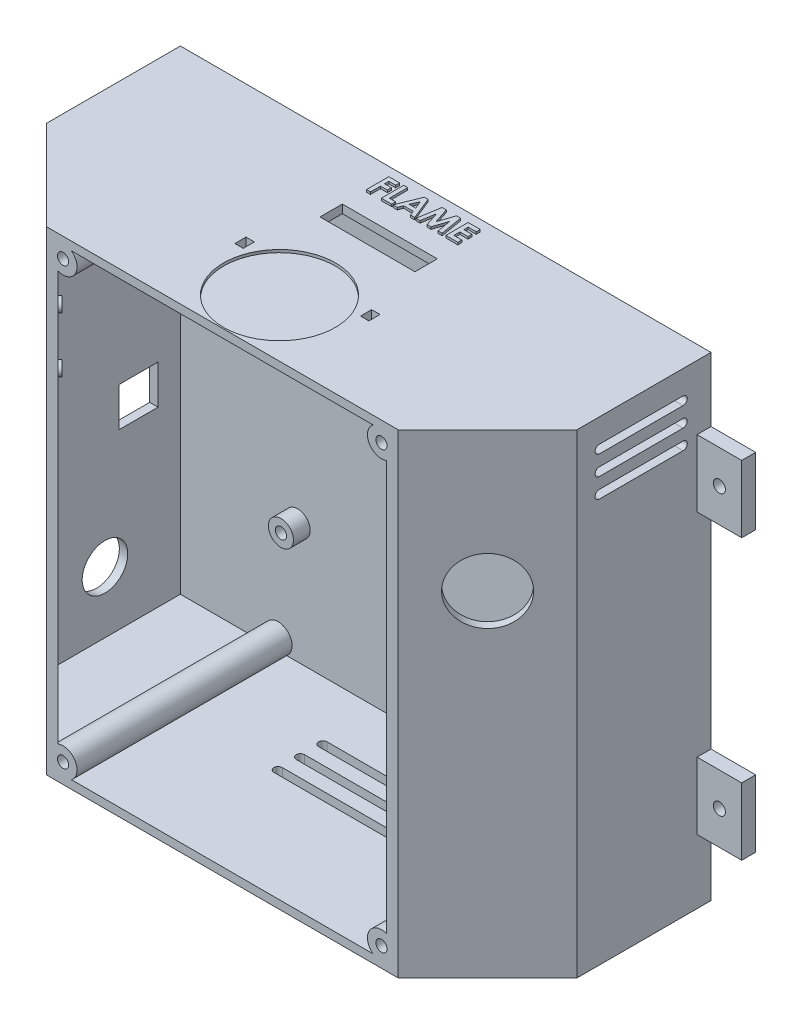
SolidWorks part; units mm, degrees
ref_plane "Front Plane" through (0, 0, 0) normal (0, 0, 1) x (1, 0, 0)
ref_plane "Top Plane" through (0, 0, 0) normal (0, 1, 0) x (1, 0, 0)
ref_plane "Right Plane" through (0, 0, 0) normal (1, 0, 0) x (0, 0, -1)
sketch "Sketch1" plane through (0, 0, 0) normal (0, 1, 0) x (1, 0, 0)
  line L0 (-95, 0) -> (95, 0)
  line L1 (95, 0) -> (95, -48)
  line L2 (95, -48) -> (63, -80)
  line L3 (63, -80) -> (-63, -80)
  line L4 (-63, -80) -> (-95, -48)
  line L5 (-95, -48) -> (-95, 0)
extrude "Block" add sketch "Sketch1" along normal blind 170
shell "Shell1" thickness 3
sketch "Sketch2" plane through (0, 0, 0) normal (0, 0, 1) x (1, 0, 0)
  circle A0 centre (-57, 7) radius 5
  circle A1 centre (57, 7) radius 5
  circle A2 centre (-57, 163) radius 5
  circle A3 centre (57, 163) radius 5
extrude "Panel columns" add sketch "Sketch2" along normal blind 80
ref_plane "P1_Front_80" through (0, 0, 80) normal (0, 0, 1) x (1, 0, 0)
sketch "Sketch3" plane through (0, 0, 80) normal (0, 0, 1) x (1, 0, 0)
  circle A0 centre (-57, 7) radius 2
  circle A1 centre (57, 7) radius 2
  circle A2 centre (-57, 163) radius 2
  circle A3 centre (57, 163) radius 2
extrude "Panel insert holes" cut sketch "Sketch3" against normal blind 7
ref_plane "P2_Front_3" through (0, 0, 3) normal (0, 0, 1) x (1, 0, 0)
sketch "Sketch4" plane through (0, 0, 3) normal (0, 0, 1) x (1, 0, 0)
  circle A0 centre (-50, 46) radius 4.5
  circle A1 centre (50, 46) radius 4.5
  circle A2 centre (-50, 150) radius 4.5
  circle A3 centre (50, 150) radius 4.5
extrude "Plate bosses" add sketch "Sketch4" along normal blind 6
ref_plane "P3_Front_9" through (0, 0, 9) normal (0, 0, 1) x (1, 0, 0)
sketch "Sketch5" plane through (0, 0, 9) normal (0, 0, 1) x (1, 0, 0)
  circle A0 centre (-50, 46) radius 2
  circle A1 centre (50, 46) radius 2
  circle A2 centre (-50, 150) radius 2
  circle A3 centre (50, 150) radius 2
extrude "Plate insert holes" cut sketch "Sketch5" against normal blind 7
ref_plane "P4_Right_-95" through (-95, 0, 0) normal (1, 0, 0) x (0, 0, -1)
sketch "Sketch6" plane through (-95, 0, 0) normal (1, 0, 0) x (0, 0, -1)
  line L1 (-25, 65) -> (-11, 65)
  line L2 (-25, 65) -> (-25, 79)
  line L3 (-25, 79) -> (-11, 79)
  line L4 (-11, 65) -> (-11, 79)
  line L5 (-25, 65) -> (-11, 79) construction
  line L6 (-25, 79) -> (-11, 65) construction
  point P0 (-18, 72)
extrude "USB access" cut sketch "Sketch6" along normal blind 4
ref_plane "P5_Right_-95" through (-95, 0, 0) normal (1, 0, 0) x (0, 0, -1)
sketch "Sketch7" plane through (-95, 0, 0) normal (1, 0, 0) x (0, 0, -1)
  circle A0 centre (-30, 25) radius 8.15
extrude "DC in" cut sketch "Sketch7" along normal blind 4
sketch "Sketch8" plane through (0, 0, 0) normal (0, 1, 0) x (1, 0, 0)
  line L0 (-20, -24) -> (20, -24) construction
  line L1 (-20, -22.5) -> (20, -22.5)
  line L2 (-20, -25.5) -> (20, -25.5)
  line L3 (-20, -32) -> (20, -32) construction
  line L4 (-20, -30.5) -> (20, -30.5)
  line L5 (-20, -33.5) -> (20, -33.5)
  line L6 (-20, -40) -> (20, -40) construction
  line L7 (-20, -38.5) -> (20, -38.5)
  line L8 (-20, -41.5) -> (20, -41.5)
  arc A0 (-20, -22.5) -> (-20, -25.5) centre (-20, -24) ccw
  arc A1 (20, -25.5) -> (20, -22.5) centre (20, -24) ccw
  arc A2 (-20, -30.5) -> (-20, -33.5) centre (-20, -32) ccw
  arc A3 (20, -33.5) -> (20, -30.5) centre (20, -32) ccw
  arc A4 (-20, -38.5) -> (-20, -41.5) centre (-20, -40) ccw
  arc A5 (20, -41.5) -> (20, -38.5) centre (20, -40) ccw
  point P2 (0, -24)
  point P7 (0, -32)
  point P14 (0, -40)
  point P21 (0, 0)
extrude "Intake slots" cut sketch "Sketch8" along normal blind 4
ref_plane "P6_Right_-95" through (-95, 0, 0) normal (1, 0, 0) x (0, 0, -1)
sketch "Sketch9" plane through (-95, 0, 0) normal (1, 0, 0) x (0, 0, -1)
  line L0 (-10, 146) -> (-40, 146) construction
  line L1 (-10, 144.5) -> (-40, 144.5)
  line L2 (-10, 147.5) -> (-40, 147.5)
  line L3 (-10, 153) -> (-40, 153) construction
  line L4 (-10, 151.5) -> (-40, 151.5)
  line L5 (-10, 154.5) -> (-40, 154.5)
  line L6 (-10, 160) -> (-40, 160) construction
  line L7 (-10, 158.5) -> (-40, 158.5)
  line L8 (-10, 161.5) -> (-40, 161.5)
  arc A0 (-10, 144.5) -> (-10, 147.5) centre (-10, 146) ccw
  arc A1 (-40, 147.5) -> (-40, 144.5) centre (-40, 146) ccw
  arc A2 (-10, 151.5) -> (-10, 154.5) centre (-10, 153) ccw
  arc A3 (-40, 154.5) -> (-40, 151.5) centre (-40, 153) ccw
  arc A4 (-10, 158.5) -> (-10, 161.5) centre (-10, 160) ccw
  arc A5 (-40, 161.5) -> (-40, 158.5) centre (-40, 160) ccw
  point P2 (-25, 146)
  point P7 (-25, 153)
  point P14 (-25, 160)
  point P21 (0, 0)
extrude "Outlet slots left" cut sketch "Sketch9" along normal blind 4
ref_plane "P7_Right_95" through (95, 0, 0) normal (1, 0, 0) x (0, 0, -1)
sketch "Sketch10" plane through (95, 0, 0) normal (1, 0, 0) x (0, 0, -1)
  line L0 (-10, 146) -> (-40, 146) construction
  line L1 (-10, 144.5) -> (-40, 144.5)
  line L2 (-10, 147.5) -> (-40, 147.5)
  line L3 (-10, 153) -> (-40, 153) construction
  line L4 (-10, 151.5) -> (-40, 151.5)
  line L5 (-10, 154.5) -> (-40, 154.5)
  line L6 (-10, 160) -> (-40, 160) construction
  line L7 (-10, 158.5) -> (-40, 158.5)
  line L8 (-10, 161.5) -> (-40, 161.5)
  arc A0 (-10, 144.5) -> (-10, 147.5) centre (-10, 146) ccw
  arc A1 (-40, 147.5) -> (-40, 144.5) centre (-40, 146) ccw
  arc A2 (-10, 151.5) -> (-10, 154.5) centre (-10, 153) ccw
  arc A3 (-40, 154.5) -> (-40, 151.5) centre (-40, 153) ccw
  arc A4 (-10, 158.5) -> (-10, 161.5) centre (-10, 160) ccw
  arc A5 (-40, 161.5) -> (-40, 158.5) centre (-40, 160) ccw
  point P2 (-25, 146)
  point P7 (-25, 153)
  point P14 (-25, 160)
  point P21 (0, 0)
extrude "Outlet slots right" cut sketch "Sketch10" against normal blind 4
ref_plane "P8_Top_170" through (0, 170, 0) normal (0, 1, 0) x (1, 0, 0)
sketch "Sketch11" plane through (0, 170, 0) normal (0, 1, 0) x (1, 0, 0)
  circle A0 centre (0, -59.5) radius 20.025
extrude "Flame pocket" cut sketch "Sketch11" against normal blind 1
sketch "Sketch12" plane through (0, 170, 0) normal (0, 1, 0) x (1, 0, 0)
  line L1 (-24, -51.5) -> (-21, -51.5)
  line L2 (-24, -51.5) -> (-24, -47.5)
  line L3 (-24, -47.5) -> (-21, -47.5)
  line L4 (-21, -51.5) -> (-21, -47.5)
  line L5 (-24, -51.5) -> (-21, -47.5) construction
  line L6 (-24, -47.5) -> (-21, -51.5) construction
  line L7 (21, -51.5) -> (24, -51.5)
  line L8 (21, -51.5) -> (21, -47.5)
  line L9 (21, -47.5) -> (24, -47.5)
  line L10 (24, -51.5) -> (24, -47.5)
  line L11 (21, -51.5) -> (24, -47.5) construction
  line L12 (21, -47.5) -> (24, -51.5) construction
  line L13 (-17, -28) -> (17, -28)
  line L14 (-17, -28) -> (-17, -20)
  line L15 (-17, -20) -> (17, -20)
  line L16 (17, -28) -> (17, -20)
  line L17 (-17, -28) -> (17, -20) construction
  line L18 (-17, -20) -> (17, -28) construction
  point P0 (-22.5, -49.5)
  point P5 (22.5, -49.5)
  point P10 (0, -24)
extrude "Flame tie + wire slots" cut sketch "Sketch12" against normal blind 4
sketch "Sketch13" plane through (0, 170, 0) normal (0, 1, 0) x (1, 0, 0)
  text T0 "FLAME" font "Century Gothic" height 8
extrude "FLAME label (raised)" add sketch "Sketch13" along normal blind 0.8
sketch "Sketch14" plane through (0, 0, 0) normal (0, 1, 0) x (1, 0, 0)
  circle A0 centre (-80, -10) radius 5
  circle A1 centre (-80, -40) radius 5
  circle A2 centre (80, -10) radius 5
  circle A3 centre (80, -40) radius 5
extrude "Feet" add sketch "Sketch14" against normal blind 3
sketch "Sketch15" plane through (0, 0, 0) normal (0, 0, 1) x (1, 0, 0)
  line L1 (-111, 23) -> (-95, 23)
  line L2 (-111, 23) -> (-111, 47)
  line L3 (-111, 47) -> (-95, 47)
  line L4 (-95, 23) -> (-95, 47)
  line L6 (95, 23) -> (111, 23)
  line L7 (95, 23) -> (95, 47)
  line L8 (95, 47) -> (111, 47)
  line L9 (111, 23) -> (111, 47)
  line L11 (-111, 123) -> (-95, 123)
  line L12 (-111, 123) -> (-111, 147)
  line L13 (-111, 147) -> (-95, 147)
  line L14 (-95, 123) -> (-95, 147)
  line L16 (95, 123) -> (111, 123)
  line L17 (95, 123) -> (95, 147)
  line L18 (95, 147) -> (111, 147)
  line L19 (111, 123) -> (111, 147)
extrude "Wall ears" add sketch "Sketch15" along normal blind 5
sketch "Sketch16" plane through (0, 0, 0) normal (0, 0, 1) x (1, 0, 0)
  circle A0 centre (-103, 35) radius 2.15
  circle A1 centre (103, 35) radius 2.15
  circle A2 centre (-103, 135) radius 2.15
  circle A3 centre (103, 135) radius 2.15
extrude "Wall ear screw holes" cut sketch "Sketch16" along normal through all
sketch "Sketch17" plane through (-71.5, 0, 71.5) normal (-0.7071, 0, 0.7071) x (0.7071, 0, 0.7071)
  circle A0 centre (-10.6066, 120) radius 11.65
extrude "PIR 1 (left) dome hole" cut sketch "Sketch17" against normal blind 4
sketch "Sketch18" plane through (-69.3787, 0, 69.3787) normal (0.7071, 0, -0.7071) x (-0.7071, 0, -0.7071)
  circle A0 centre (24.6066, 120) radius 2.2
  circle A1 centre (-3.3934, 120) radius 2.2
extrude "PIR 1 (left) bosses" add sketch "Sketch18" along normal blind 1
sketch "Sketch19" plane through (-68.6716, 0, 68.6716) normal (0.7071, 0, -0.7071) x (-0.7071, 0, -0.7071)
  circle A0 centre (24.6066, 120) radius 0.8
  circle A1 centre (-3.3934, 120) radius 0.8
extrude "PIR 1 (left) M2 pilots" cut sketch "Sketch19" against normal blind 3
sketch "Sketch20" plane through (71.5, 0, 71.5) normal (0.7071, 0, 0.7071) x (0.7071, 0, -0.7071)
  circle A0 centre (10.6066, 120) radius 11.65
extrude "PIR 2 (right) dome hole" cut sketch "Sketch20" against normal blind 4
sketch "Sketch21" plane through (69.3787, 0, 69.3787) normal (-0.7071, 0, -0.7071) x (-0.7071, 0, 0.7071)
  circle A0 centre (-24.6066, 120) radius 2.2
  circle A1 centre (3.3934, 120) radius 2.2
extrude "PIR 2 (right) bosses" add sketch "Sketch21" along normal blind 1
sketch "Sketch22" plane through (68.6716, 0, 68.6716) normal (-0.7071, 0, -0.7071) x (-0.7071, 0, 0.7071)
  circle A0 centre (-24.6066, 120) radius 0.8
  circle A1 centre (3.3934, 120) radius 0.8
extrude "PIR 2 (right) M2 pilots" cut sketch "Sketch22" against normal blind 3
